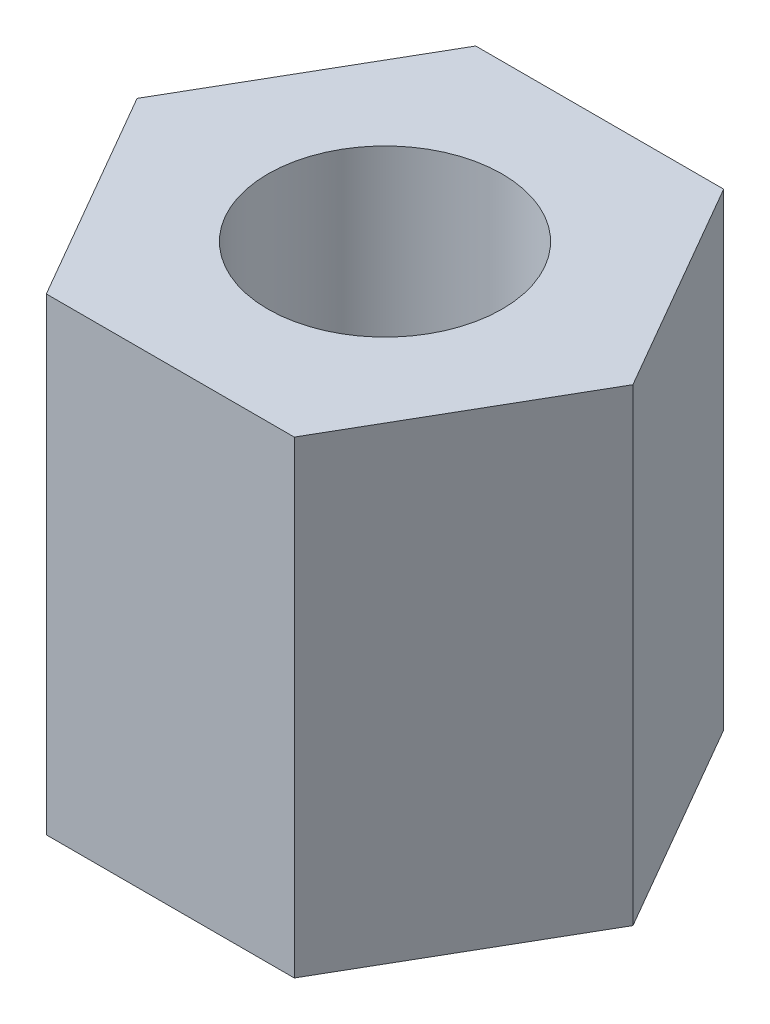
SolidWorks part; units mm, degrees
ref_plane "前视基准面" through (0, 0, 0) normal (0, 0, 1) x (1, 0, 0)
ref_plane "上视基准面" through (0, 0, 0) normal (0, 1, 0) x (1, 0, 0)
ref_plane "右视基准面" through (0, 0, 0) normal (1, 0, 0) x (0, 0, -1)
sketch "草图1" plane through (0, 0, 0) normal (0, 1, 0) x (1, 0, 0)
  line L1 (-4.1472, 7.5722) -> (-5.7349, 10.3222)
  line L2 (-5.7349, 10.3222) -> (-8.9103, 10.3222)
  line L3 (-8.9103, 10.3222) -> (-10.498, 7.5722)
  line L4 (-10.498, 7.5722) -> (-8.9103, 4.8222)
  line L5 (-8.9103, 4.8222) -> (-5.7349, 4.8222)
  line L6 (-5.7349, 4.8222) -> (-4.1472, 7.5722)
  circle A0 centre (-7.3226, 7.5722) radius 1.5
  circle A1 centre (-7.3226, 7.5722) radius 2.75 construction
extrude "凸台-拉伸1" add sketch "草图1" along normal blind 6
